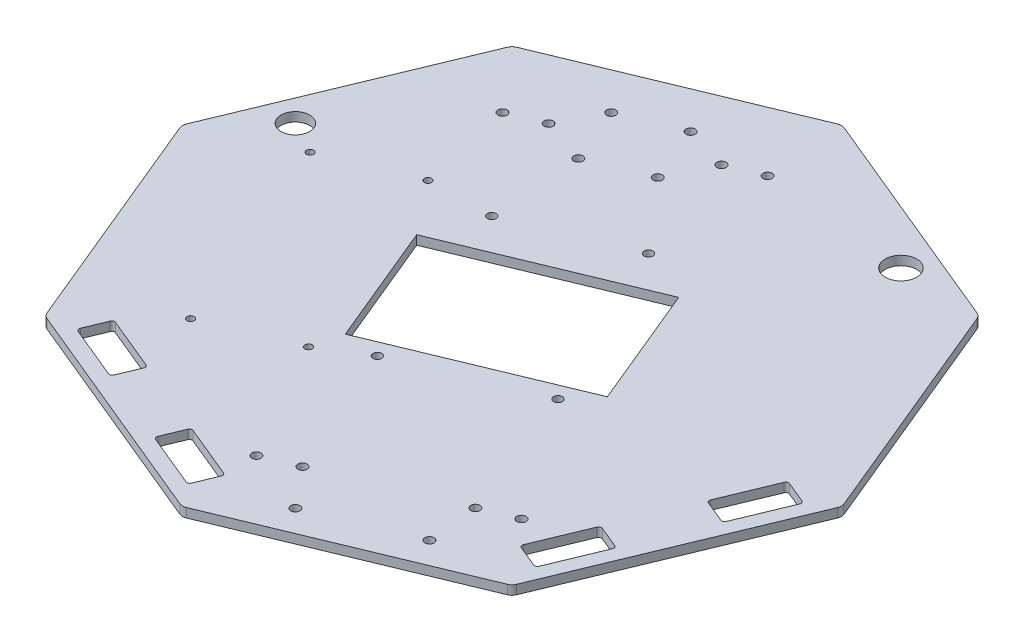
SolidWorks part; units mm, degrees
ref_plane "Front Plane" through (0, 0, 0) normal (0, 0, 1) x (1, 0, 0)
ref_plane "Top Plane" through (0, 0, 0) normal (0, 1, 0) x (1, 0, 0)
ref_plane "Right Plane" through (0, 0, 0) normal (1, 0, 0) x (0, 0, -1)
sketch "Sketch1" plane through (0, 0, 0) normal (0, 1, 0) x (1, 0, 0)
  line L1 (115.2748, 0) -> (81.5116, 81.5116)
  line L2 (81.5116, 81.5116) -> (0, 115.2748)
  line L3 (0, 115.2748) -> (-81.5116, 81.5116)
  line L4 (-81.5116, 81.5116) -> (-115.2748, 0)
  line L5 (-115.2748, 0) -> (-81.5116, -81.5116)
  line L6 (-81.5116, -81.5116) -> (0, -115.2748)
  line L7 (0, -115.2748) -> (81.5116, -81.5116)
  line L8 (81.5116, -81.5116) -> (115.2748, 0)
  circle A0 centre (0, 0) radius 106.5 construction
  dimension "D1" = 213
extrude "Boss-Extrude1" add sketch "Sketch1" along normal blind 3.175
sketch "Sketch2" plane through (0, 3.175, 0) normal (0, 1, 0) x (1, 0, 0)
  line L0 (0, 0) -> (98.3932, 40.7558) construction
  line L1 (115.2748, 0) -> (81.5116, 81.5116) construction
  line L2 (0, 0) -> (34.1835, 14.1593) construction
  line L3 (0, 0) -> (-30.232, 72.9865) construction
  line L4 (34.1835, 14.1593) -> (3.9516, 87.1458) construction
  line L5 (-30.232, 72.9865) -> (3.9516, 87.1458) construction
  line L6 (21.2492, 8.8017) -> (-8.9828, 81.7882) construction
  circle A0 centre (-8.9828, 81.7882) radius 1.6
  circle A1 centre (3.9516, 87.1458) radius 1.6
  circle A2 centre (-64.4155, 58.8272) radius 1.6
  circle A3 centre (-51.4812, 64.1848) radius 1.6
  circle A4 centre (64.4155, -58.8272) radius 1.6
  circle A5 centre (51.4812, -64.1848) radius 1.6
  circle A6 centre (8.9828, -81.7882) radius 1.6
  circle A7 centre (-3.9516, -87.1458) radius 1.6
  dimension "D4" = 3.2
  dimension "D1" = 79
  dimension "D2" = 37
  dimension "D3" = 23
extrude "Cut-Extrude1" cut sketch "Sketch2" against normal through all
sketch "Sketch3" plane through (0, 3.175, 0) normal (0, 1, 0) x (1, 0, 0)
  line L0 (0, 0) -> (98.3932, 40.7558) construction
  line L1 (115.2748, 0) -> (81.5116, 81.5116) construction
  line L2 (-79.9156, 33.1021) -> (-98.3932, 40.7558) construction
  line L3 (93.6269, 0) -> (66.2042, 66.2042) construction
  line L4 (66.2042, 66.2042) -> (0, 93.6269) construction
  line L5 (0, 93.6269) -> (-66.2042, 66.2042) construction
  line L6 (-66.2042, 66.2042) -> (-93.6269, 0) construction
  line L7 (-93.6269, 0) -> (-66.2042, -66.2042) construction
  line L8 (-66.2042, -66.2042) -> (0, -93.6269) construction
  line L9 (0, -93.6269) -> (66.2042, -66.2042) construction
  line L10 (66.2042, -66.2042) -> (93.6269, 0) construction
  line L11 (-81.5116, 81.5116) -> (-115.2748, 0) construction
  line L12 (-93.6269, 0) -> (-112.1045, 7.6537) construction
  line L13 (-102.8657, 3.8268) -> (-89.1544, 36.929) construction
  line L14 (33.1021, -79.9156) -> (40.7558, -98.3932) construction
  line L15 (0, -115.2748) -> (81.5116, -81.5116) construction
  line L16 (0, -93.6269) -> (7.6537, -112.1045) construction
  line L17 (3.8268, -102.8657) -> (36.929, -89.1544) construction
  line L18 (-51.4812, 64.1848) -> (-8.9828, 81.7882) construction
  line L19 (-30.232, 72.9865) -> (-20.4328, 77.0455) construction
  line L20 (-30.232, 72.9865) -> (-34.291, 82.7857) construction
  line L21 (-20.4328, 77.0455) -> (-24.4917, 86.8447) construction
  line L22 (-34.291, 82.7857) -> (-24.4917, 86.8447) construction
  line L23 (33.1021, 79.9156) -> (40.7558, 98.3932) construction
  line L24 (81.5116, 81.5116) -> (0, 115.2748) construction
  line L25 (66.2042, 66.2042) -> (73.8579, 84.6818) construction
  line L26 (70.0311, 75.443) -> (36.929, 89.1544) construction
  line L27 (-66.2042, -66.2042) -> (-73.8579, -84.6818) construction
  line L28 (-81.5116, -81.5116) -> (0, -115.2748) construction
  line L29 (0, -93.6269) -> (-7.6537, -112.1045) construction
  line L30 (-3.8268, -102.8657) -> (-70.0311, -75.443) construction
  line L31 (-3.8268, -102.8657) -> (-5.7403, -107.4851) construction
  line L32 (-68.1177, -70.8236) -> (-71.9445, -80.0624)
  line L33 (-5.7403, -107.4851) -> (-71.9445, -80.0624) construction
  line L34 (-51.9445, -88.3467) -> (-48.1177, -79.1079)
  line L35 (-38.8424, -93.7738) -> (-33.1021, -79.9156) construction
  line L36 (-51.9445, -88.3467) -> (-71.9445, -80.0624)
  line L37 (-48.1177, -79.1079) -> (-68.1177, -70.8236)
  line L38 (-1.9134, -98.2463) -> (-5.7403, -107.4851)
  line L39 (-21.9134, -89.9621) -> (-1.9134, -98.2463)
  line L40 (-25.7403, -99.2008) -> (-21.9134, -89.9621)
  line L41 (-25.7403, -99.2008) -> (-5.7403, -107.4851)
  line L42 (88.3467, -51.9445) -> (80.0624, -71.9445)
  line L43 (70.8236, -68.1177) -> (80.0624, -71.9445)
  line L44 (79.1079, -48.1177) -> (70.8236, -68.1177)
  line L45 (88.3467, -51.9445) -> (79.1079, -48.1177)
  line L46 (98.2463, -1.9134) -> (107.4851, -5.7403)
  line L47 (89.9621, -21.9134) -> (98.2463, -1.9134)
  line L48 (99.2008, -25.7403) -> (89.9621, -21.9134)
  line L49 (99.2008, -25.7403) -> (107.4851, -5.7403)
  circle A0 centre (0, 0) radius 86.5 construction
  circle A1 centre (-96.01, 20.3779) radius 5
  circle A2 centre (20.3779, -96.01) radius 1.6
  circle A3 centre (53.48, -82.2987) radius 1.6
  circle A4 centre (-24.4917, 86.8447) radius 1.6
  circle A5 centre (-44.0902, 78.7267) radius 1.6
  circle A6 centre (-35.9722, 59.1283) radius 1.6
  circle A7 centre (-16.3738, 67.2462) radius 1.6
  circle A8 centre (53.48, 82.2987) radius 5.5
  point P72 (-50.0311, -83.7273)
  dimension "D2" = 10
  dimension "D3" = 3.2
  dimension "D5" = 3.2
  dimension "D6" = 11
  dimension "D1" = 173
  dimension "D4" = 15
  dimension "D7" = 5
  dimension "D8" = 20
extrude "Cut-Extrude2" cut sketch "Sketch3" against normal through all
ref_plane "Plane1" through (0, 0, 0) normal (-0.9239, 0, 0.3827) x (0.3827, 0, 0.9239)
ref_plane "Plane2" through (0, 0, 0) normal (0.3827, 0, 0.9239) x (0.9239, 0, -0.3827)
sketch "Sketch5" plane through (0, 3.175, 0) normal (0, 1, 0) x (1, 0, 0)
  circle A0 centre (33.2284, -17.1657) radius 1.524 construction
  circle A1 centre (-11.358, -35.634) radius 1.524 construction
  circle A2 centre (-33.6971, 26.594) radius 1.524 construction
  circle A3 centre (5.0227, 42.6323) radius 1.524 construction
  circle A4 centre (33.2284, -17.1657) radius 1.524
  circle A5 centre (-11.358, -35.634) radius 1.524
  circle A6 centre (-33.6971, 26.594) radius 1.524
  circle A7 centre (5.0227, 42.6323) radius 1.524
extrude "Cut-Extrude3" cut sketch "Sketch5" against normal through all
sketch "Sketch6" plane through (0, 3.175, 0) normal (0, 1, 0) x (1, 0, 0)
  line L0 (-98.3932, -40.7558) -> (98.3932, 40.7558) construction
  line L1 (-115.2748, 0) -> (-81.5116, -81.5116) construction
  line L2 (115.2748, 0) -> (81.5116, 81.5116) construction
  line L3 (0, 0) -> (32.3358, 13.3939) construction
  line L4 (0, 0) -> (-8.8017, 21.2492) construction
  line L5 (41.1375, -7.8553) -> (23.5341, 34.6431)
  line L6 (-41.1375, 7.8553) -> (23.5341, 34.6431)
  line L7 (-23.5341, -34.6431) -> (-41.1375, 7.8553)
  line L8 (-23.5341, -34.6431) -> (41.1375, -7.8553)
  point P15 (-32.3358, -13.3939)
  dimension "D1" = 23
  dimension "D2" = 35
extrude "Cut-Extrude4" cut sketch "Sketch6" against normal through all
sketch "Sketch8" plane through (0, 3.175, 0) normal (0, 1, 0) x (1, 0, 0)
  circle A0 centre (-55.2085, -56.9635) radius 1.25 construction
  circle A1 centre (-26.1063, -44.9089) radius 1.25 construction
  circle A2 centre (-84.6751, 14.1753) radius 1.25 construction
  circle A3 centre (-55.5729, 26.2298) radius 1.25 construction
  circle A4 centre (-55.2085, -56.9635) radius 1.25
  circle A5 centre (-26.1063, -44.9089) radius 1.25
  circle A6 centre (-84.6751, 14.1753) radius 1.25
  circle A7 centre (-55.5729, 26.2298) radius 1.25
extrude "Cut-Extrude5" cut sketch "Sketch8" against normal through all
sketch "Sketch9" plane through (0, 3.175, 0) normal (0, 1, 0) x (1, 0, 0)
  line L1 (-44.5184, 54.7484) -> (-72.4601, 54.7484)
  line L2 (-44.5184, 54.7484) -> (-44.5184, 68.2262)
  line L3 (-44.5184, 68.2262) -> (-72.4601, 68.2262)
  line L4 (-72.4601, 54.7484) -> (-72.4601, 68.2262)
  line L5 (-44.5184, 54.7484) -> (-72.4601, 68.2262) construction
  line L6 (-44.5184, 68.2262) -> (-72.4601, 54.7484) construction
  line L7 (18.597, 74.1433) -> (-11.6458, 74.1433)
  line L8 (18.597, 74.1433) -> (18.597, 91.3466)
  line L9 (18.597, 91.3466) -> (-11.6458, 91.3466)
  line L10 (-11.6458, 74.1433) -> (-11.6458, 91.3466)
  line L11 (18.597, 74.1433) -> (-11.6458, 91.3466) construction
  line L12 (18.597, 91.3466) -> (-11.6458, 74.1433) construction
  line L13 (14.3562, -91.9819) -> (-9.1247, -91.9819)
  line L14 (14.3562, -91.9819) -> (14.3562, -76.5567)
  line L15 (14.3562, -76.5567) -> (-9.1247, -76.5567)
  line L16 (-9.1247, -91.9819) -> (-9.1247, -76.5567)
  line L17 (14.3562, -91.9819) -> (-9.1247, -76.5567) construction
  line L18 (14.3562, -76.5567) -> (-9.1247, -91.9819) construction
  line L19 (66.4561, -68.6488) -> (39.1809, -68.6488)
  line L20 (66.4561, -68.6488) -> (66.4561, -51.8149)
  line L21 (66.4561, -51.8149) -> (39.1809, -51.8149)
  line L22 (39.1809, -68.6488) -> (39.1809, -51.8149)
  line L23 (66.4561, -68.6488) -> (39.1809, -51.8149) construction
  line L24 (66.4561, -51.8149) -> (39.1809, -68.6488) construction
  point P4 (-58.4892, 61.4873)
  point P9 (3.4756, 82.7449)
  point P14 (2.6158, -84.2693)
  point P19 (52.8185, -60.2318)
extrude "Boss-Extrude2" add sketch "Sketch9" against normal up to surface (3.175 mm away) up to face at (-26.1063, 0, 46.1589)
sketch "Sketch16" plane through (0, 3.175, 0) normal (0, 1, 0) x (1, 0, 0)
  line L0 (0, 0) -> (-40.7558, 98.3932) construction
  line L1 (0, 115.2748) -> (-81.5116, 81.5116) construction
  line L2 (-40.7558, 98.3932) -> (40.7558, -98.3932) construction
  line L3 (0, -115.2748) -> (81.5116, -81.5116) construction
  line L4 (-98.3932, -40.7558) -> (98.3932, 40.7558) construction
  line L5 (-115.2748, 0) -> (-81.5116, -81.5116) construction
  line L6 (115.2748, 0) -> (81.5116, 81.5116) construction
  line L7 (-51.719, 64.4976) -> (-30.3774, 73.3376) construction
  line L8 (-30.3774, 73.3376) -> (-96.1888, 46.0776) construction
  line L9 (-81.5116, 81.5116) -> (-115.2748, 0) construction
  circle A0 centre (-51.719, 64.4976) radius 1.6
  circle A1 centre (-63.0827, 59.7906) radius 1.6
  circle A2 centre (-9.0358, 82.1775) radius 1.6
  circle A3 centre (2.3279, 86.8846) radius 1.6
  circle A4 centre (63.0827, -59.7906) radius 1.6
  circle A5 centre (51.719, -64.4976) radius 1.6
  circle A6 centre (9.0358, -82.1775) radius 1.6
  circle A7 centre (-2.3279, -86.8846) radius 1.6
  dimension "D3" = 3.2
  dimension "D1" = 23.1
  dimension "D2" = 79.38
  dimension "D4" = 12.3
extrude "Cut-Extrude6" cut sketch "Sketch16" against normal blind 10
fillet "Fillet1" radius 3 8 edges at (-81.5116, 1.5875, 81.5116) (0, 1.5875, 115.2748) (81.5116, 1.5875, 81.5116) (115.2748, 1.5875, 0) (81.5116, 1.5875, -81.5116) (0, 1.5875, -115.2748) (-81.5116, 1.5875, -81.5116) (-115.2748, 1.5875, 0)
fillet "Fillet2" radius 1 16 edges at (89.9621, 1.5875, 21.9134) (99.2008, 1.5875, 25.7403) (107.4851, 1.5875, 5.7403) (98.2463, 1.5875, 1.9134) (70.8236, 1.5875, 68.1177) (80.0624, 1.5875, 71.9445) (88.3467, 1.5875, 51.9445) (79.1079, 1.5875, 48.1177) (-5.7403, 1.5875, 107.4851) (-1.9134, 1.5875, 98.2463) (-21.9134, 1.5875, 89.9621) (-25.7403, 1.5875, 99.2008) (-51.9445, 1.5875, 88.3467) (-71.9445, 1.5875, 80.0624) (-48.1177, 1.5875, 79.1079) (-68.1177, 1.5875, 70.8236)
